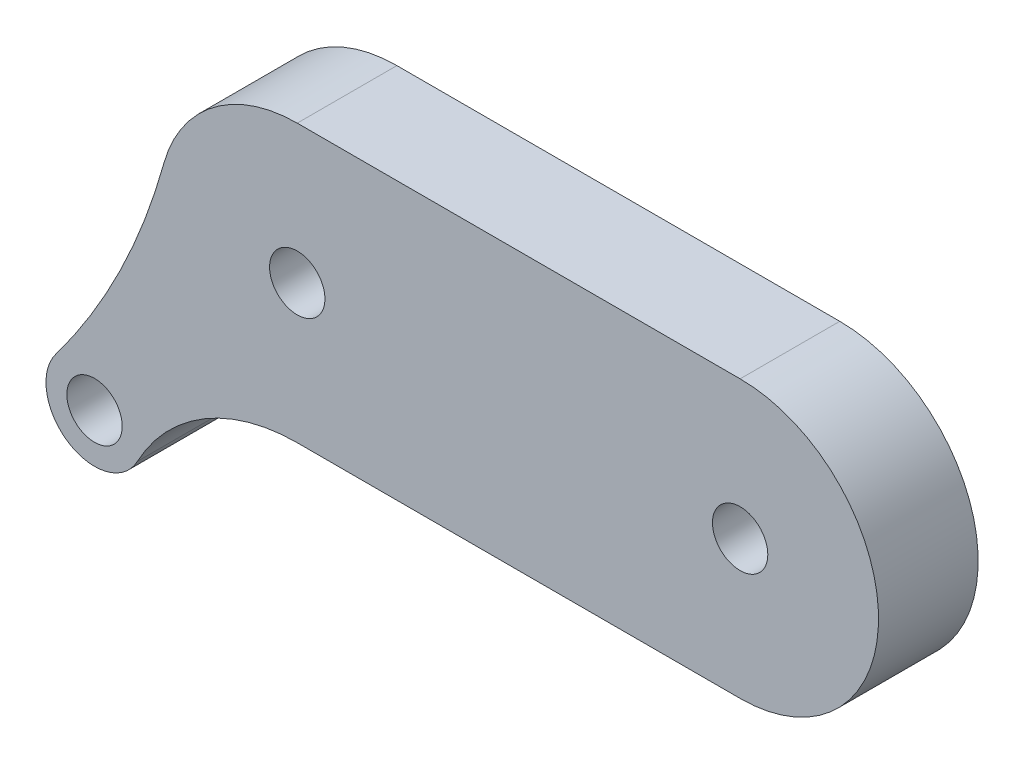
SolidWorks part; units mm, degrees
ref_plane "Front Plane" through (0, 0, 0) normal (0, 0, 1) x (1, 0, 0)
ref_plane "Top Plane" through (0, 0, 0) normal (0, 1, 0) x (1, 0, 0)
ref_plane "Right Plane" through (0, 0, 0) normal (1, 0, 0) x (0, 0, -1)
sketch "Sketch1" plane through (0, 0, 0) normal (0, 0, 1) x (1, 0, 0)
  line L0 (0, 0) -> (16, 0) construction
  line L1 (0, 5) -> (16, 5)
  line L2 (0, -5) -> (16, -5)
  arc A0 (0, 5) -> (-4.8184, 1.3353) centre (0, 0) ccw
  arc A1 (16, -5) -> (16, 5) centre (16, 0) ccw
  circle A6 centre (-7.3239, -7.6476) radius 1
  circle A7 centre (0, 0) radius 1
  circle A8 centre (16, 0) radius 1
  arc A9 (-4.8184, 1.3353) -> (-8.7251, -6.5926) centre (-27.6645, 7.6668) cw
  arc A10 (-8.7251, -6.5926) -> (-5.7751, -8.4707) centre (-7.3239, -7.6476) ccw
  arc A11 (-5.7751, -8.4707) -> (0, -5) centre (0, -11.54) cw
  point P2 (8, 0)
  dimension "D3" = 2
  dimension "D4" = 5
  dimension "D10" = 5
  dimension "D2" = 5
  dimension "D1" = 16
  dimension "D5" = 7.3239
  dimension "D6" = 7.6476
  dimension "D7" = 16
  dimension "D12" = 16
extrude "Boss-Extrude1" add sketch "Sketch1" along normal blind 3.6
